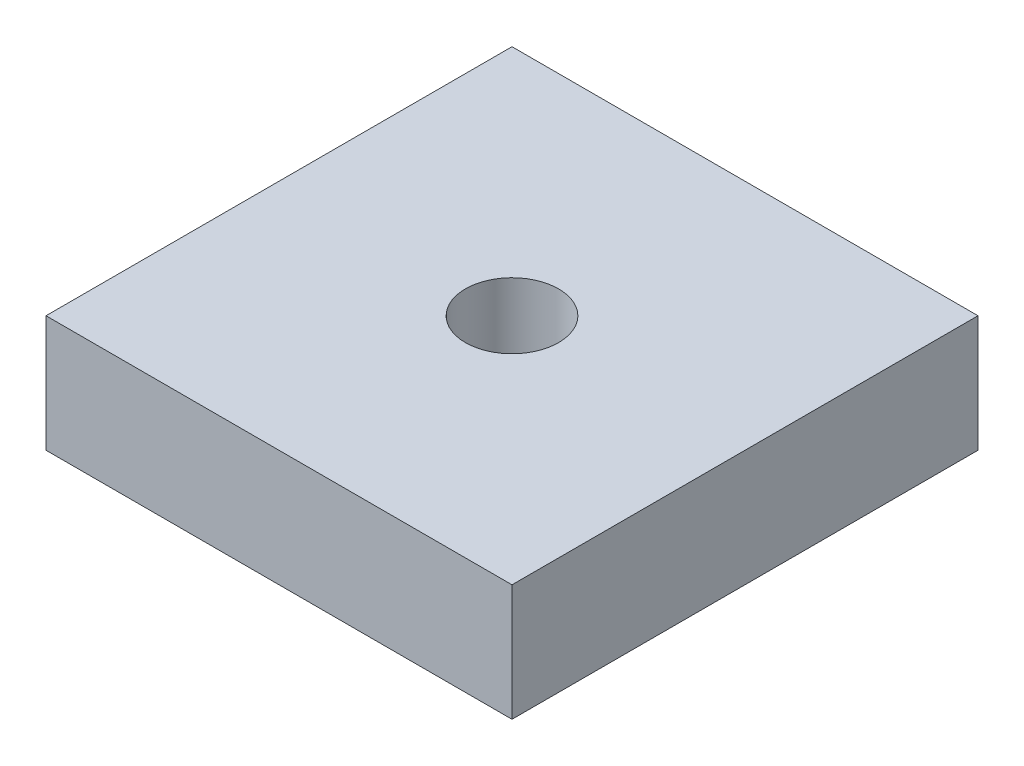
SolidWorks part; units mm, degrees
ref_plane "Front Plane" through (0, 0, 0) normal (0, 0, 1) x (1, 0, 0)
ref_plane "Top Plane" through (0, 0, 0) normal (0, 1, 0) x (1, 0, 0)
ref_plane "Right Plane" through (0, 0, 0) normal (1, 0, 0) x (0, 0, -1)
sketch "Sketch1" plane through (0, 0, 0) normal (0, 1, 0) x (1, 0, 0)
  line L1 (-10, -10) -> (10, -10)
  line L2 (-10, -10) -> (-10, 10)
  line L3 (-10, 10) -> (10, 10)
  line L4 (10, -10) -> (10, 10)
  line L5 (-10, -10) -> (10, 10) construction
  line L6 (-10, 10) -> (10, -10) construction
  circle A0 centre (0, 0) radius 2
  point P0 (0, 0)
  dimension "D2" = 4
  dimension "D1" = 20
extrude "Boss-Extrude1" add sketch "Sketch1" along normal blind 5
